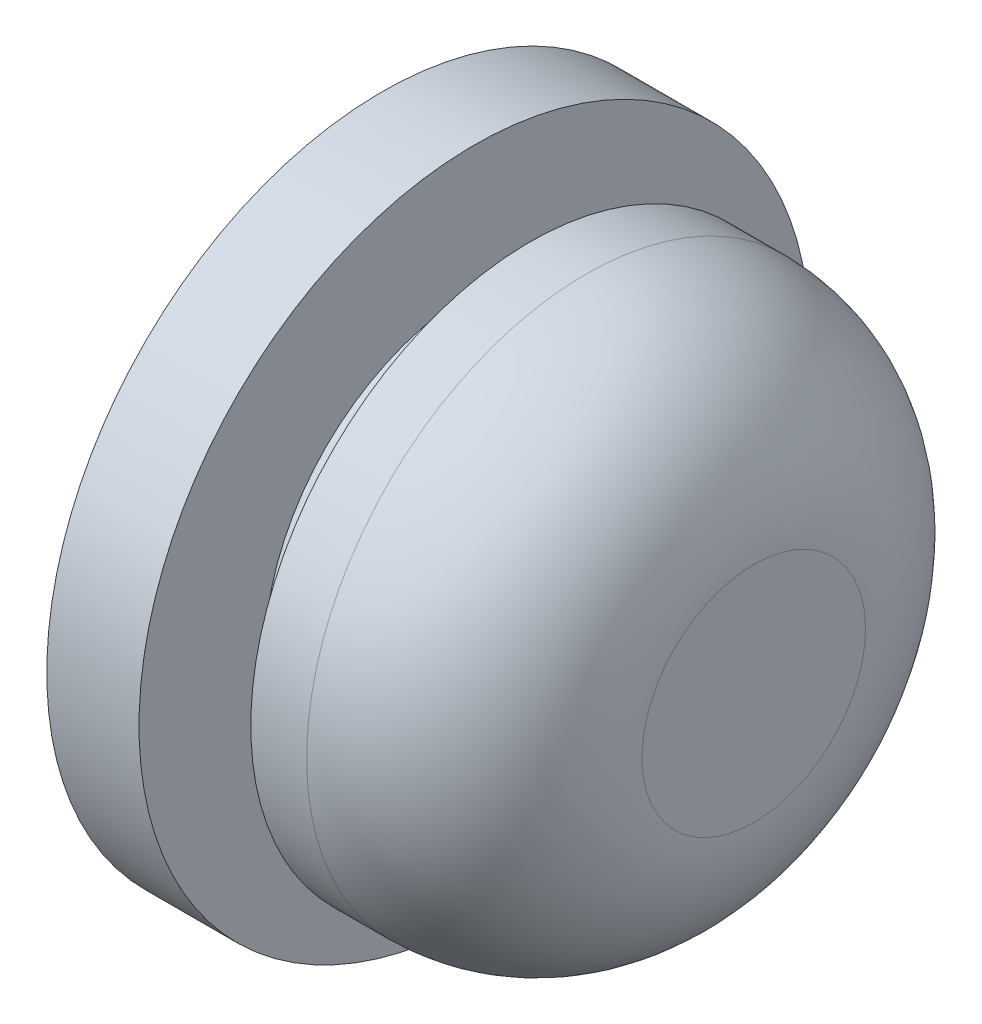
SolidWorks part; units mm, degrees
ref_plane "Спереди" through (0, 0, 0) normal (0, 0, 1) x (1, 0, 0)
ref_plane "Сверху" through (0, 0, 0) normal (0, 1, 0) x (1, 0, 0)
ref_plane "Справа" through (0, 0, 0) normal (1, 0, 0) x (0, 0, -1)
sketch "Эскиз2" plane through (0, 0, 0) normal (1, 0, 0) x (0, 0, -1)
  circle A0 centre (0, 0) radius 12
  circle A1 centre (0, 0) radius 4
  dimension "D1" = 8
  dimension "D2" = 24
extrude "Бобышка-Вытянуть1" add sketch "Эскиз2" along normal blind 3.3
sketch "Эскиз3" plane through (3.3, 0, 0) normal (1, 0, 0) x (0, 0, -1)
  circle A0 centre (0, 0) radius 4
  circle A1 centre (0, 0) radius 7.5
  dimension "D1" = 15
extrude "Бобышка-Вытянуть2" add sketch "Эскиз3" along normal blind 2
sketch "Эскиз4" plane through (5.3, 0, 0) normal (1, 0, 0) x (0, 0, -1)
  circle A0 centre (0, 0) radius 10
  dimension "D1" = 20
extrude "Бобышка-Вытянуть3" add sketch "Эскиз4" along normal blind 8
fillet "Скругление1" radius 6 1 edges at (13.3, 0, -10)
